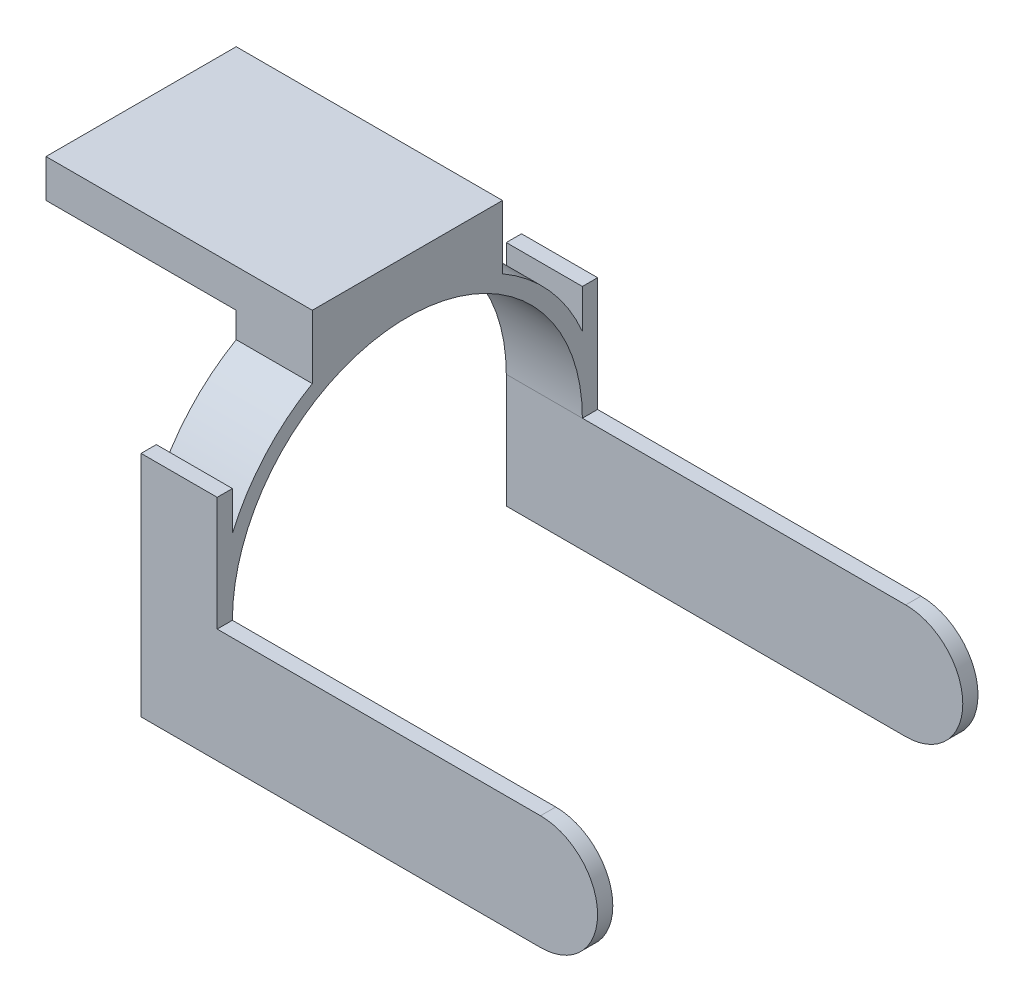
SolidWorks part; units mm, degrees
ref_plane "Front" through (0, 0, 0) normal (0, 0, 1) x (1, 0, 0)
ref_plane "Top" through (0, 0, 0) normal (0, 1, 0) x (1, 0, 0)
ref_plane "Right" through (0, 0, 0) normal (1, 0, 0) x (0, 0, -1)
sketch "草图1" plane through (0, 0, 0) normal (1, 0, 0) x (0, 0, -1)
  line L0 (0, 0) -> (-50.8301, 0) construction
  line L1 (-25, 5) -> (25, 5)
  line L2 (-25, 5) -> (-25, -5)
  line L4 (25, 5) -> (25, -5)
  line L5 (0, 0) -> (0, 38.695) construction
  line L6 (0, -5) -> (0, -75.8031) construction
  line L7 (-25, -5) -> (-25, -11.6988)
  line L8 (25, -5) -> (25, -11.6988)
  line L10 (-46, -55.0831) -> (-46, -85.0831)
  line L11 (-50, -25.0831) -> (-46, -25.0831)
  line L12 (-50, -25.0831) -> (-50, -85.0831)
  line L13 (-50, -85.0831) -> (-46, -85.0831)
  line L14 (-46, -25.0831) -> (-46, -35.3044)
  line L15 (46, -25.0831) -> (50, -25.0831)
  line L16 (46, -25.0831) -> (46, -35.3044)
  line L17 (46, -85.0831) -> (50, -85.0831)
  line L18 (50, -25.0831) -> (50, -85.0831)
  line L20 (46, -55.0831) -> (46, -85.0831)
  arc A1 (46, -55.0831) -> (-46, -55.0831) centre (0, -55.0831) ccw
  arc A3 (46, -35.3044) -> (25, -11.6988) centre (0, -55.0831) ccw
  arc A4 (-25, -11.6988) -> (-46, -35.3044) centre (0, -55.0831) ccw
  dimension "D5" = 60
  dimension "D1" = 50
  dimension "D2" = 25
  dimension "D3" = 10
  dimension "D8" = 50
  dimension "D9" = 50
  dimension "D10" = 4
  dimension "D11" = 60
extrude "凸台-拉伸1" add sketch "草图1" along normal blind 20
sketch "草图2" plane through (20, 0, 0) normal (1, 0, 0) x (0, 0, -1)
  line L0 (50, -85.0831) -> (50, -25.0831) construction
  line L1 (-50, -85.0831) -> (-46, -85.0831)
  line L2 (-50, -85.0831) -> (-50, -55.0831)
  line L3 (-50, -55.0831) -> (-46, -55.0831)
  line L4 (-46, -85.0831) -> (-46, -55.0831)
  line L5 (46, -85.0831) -> (50, -85.0831)
  line L6 (46, -85.0831) -> (46, -55.0831)
  line L7 (46, -55.0831) -> (50, -55.0831)
  line L8 (50, -85.0831) -> (50, -55.0831)
extrude "凸台-拉伸2" add sketch "草图2" along normal blind 100
sketch "草图3" plane through (0, 0, 50) normal (0, 0, 1) x (1, 0, 0)
  line L0 (120, -70.0831) -> (0, -70.0831) construction
  line L1 (120, -55.0831) -> (120, -85.0831) construction
  line L2 (0, -25.0831) -> (0, -85.0831) construction
  line L3 (120, -55.0831) -> (120, -85.0831) construction
  line L4 (105, -55.0831) -> (132.3601, -55.0831)
  line L5 (132.3601, -55.0831) -> (132.3601, -85.0831)
  line L6 (132.3601, -85.0831) -> (105, -85.0831)
  arc A0 (105, -85.0831) -> (105, -55.0831) centre (105, -70.0831) ccw
  dimension "D1" = 15
extrude "切除-拉伸1" cut sketch "草图3" against normal blind 100
sketch "草图4" plane through (0, 0, 0) normal (-1, 0, 0) x (0, 0, 1)
  line L0 (25, 5) -> (25, -11.6988) construction
  line L1 (-25, 5) -> (25, 5)
  line L2 (-25, 5) -> (-25, -5)
  line L3 (-25, -5) -> (25, -5)
  line L4 (25, 5) -> (25, -5)
  dimension "D1" = 10
extrude "凸台-拉伸3" add sketch "草图4" along normal blind 50
